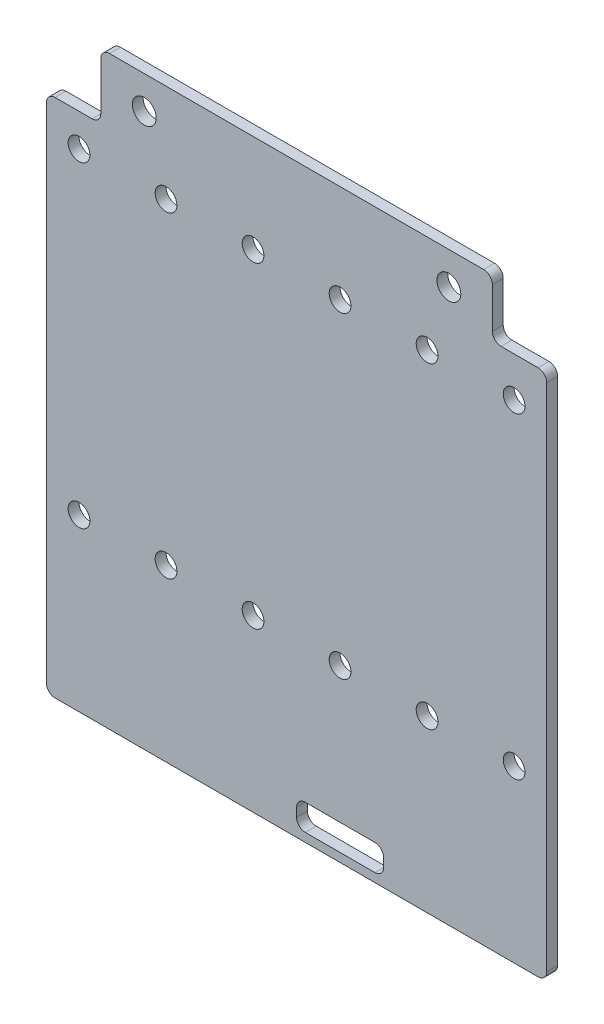
SolidWorks part; units mm, degrees
ref_plane "Front Plane" through (0, 0, 0) normal (0, 0, 1) x (1, 0, 0)
ref_plane "Top Plane" through (0, 0, 0) normal (0, 1, 0) x (1, 0, 0)
ref_plane "Right Plane" through (0, 0, 0) normal (1, 0, 0) x (0, 0, -1)
sketch "Sketch1" plane through (0, 0, 0) normal (0, 0, 1) x (1, 0, 0)
  line L0 (-63.5, -12.7) -> (63.5, -12.7) construction
  line L2 (-57.15, -3.175) -> (-57.15, 15.875)
  line L3 (-57.15, 15.875) -> (57.15, 15.875)
  line L4 (57.15, -1.0097) -> (57.15, 15.875)
  line L5 (-57.15, -3.175) -> (-73.025, -3.175)
  line L6 (-73.025, -3.175) -> (-73.025, -27.559)
  line L8 (73.025, -27.559) -> (73.025, -1.0097)
  line L9 (73.025, -1.0097) -> (57.15, -1.0097)
  line L10 (-44.45, 6.35) -> (44.45, 6.35) construction
  line L11 (-73.025, -27.559) -> (-73.025, -154.984)
  line L12 (-73.025, -154.984) -> (73.025, -154.984)
  line L13 (73.025, -154.984) -> (73.025, -27.559)
  line L17 (-63.5, -105.2) -> (63.5, -105.2) construction
  circle A0 centre (-44.45, 6.35) radius 3.4925
  circle A1 centre (44.45, 6.35) radius 3.4925
  circle A2 centre (-63.5, -12.7) radius 3.175
  circle A3 centre (-38.1, -12.7) radius 3.175
  circle A4 centre (-12.7, -12.7) radius 3.175
  circle A5 centre (12.7, -12.7) radius 3.175
  circle A6 centre (38.1, -12.7) radius 3.175
  circle A7 centre (63.5, -12.7) radius 3.175
  circle A8 centre (-63.5, -105.2) radius 3.175
  circle A9 centre (-38.1, -105.2) radius 3.175
  circle A10 centre (-12.7, -105.2) radius 3.175
  circle A11 centre (12.7, -105.2) radius 3.175
  circle A12 centre (38.1, -105.2) radius 3.175
  circle A13 centre (63.5, -105.2) radius 3.175
  point P0 (0, 0)
  point P12 (0, -12.7)
  point P27 (0, 15.875)
  dimension "D1" = 6.985
  dimension "D2" = 6.35
  dimension "0." = 6.985
  dimension "D7" = 6
  dimension "D15" = 6.35
  dimension "D3" = 88.9
  dimension "D4" = 114.3
  dimension "D5" = 0
  dimension "D6" = 146.05
  dimension "D8" = 0
  dimension "D9" = 9.525
  dimension "D10" = 28.575
  dimension "D11" = 9.525
  dimension "D14" = 92.5
  dimension "D18" = 49.784
  dimension "D16" = 6
extrude "Boss-Extrude1" add sketch "Sketch1" along normal blind 3.175
fillet "Fillet2" radius 2.54 6 edges at (57.15, 15.875, 1.5875) (73.025, -1.0097, 1.5875) (73.025, -154.984, 1.5875) (-73.025, -154.984, 1.5875) (-73.025, -3.175, 1.5875) (-57.15, 15.875, 1.5875)
sketch "Sketch3" plane through (0, 0, 3.175) normal (0, 0, 1) x (1, 0, 0)
  line L0 (-44.45, 6.35) -> (130.219, -168.319) construction
  line L1 (-44.45, 6.35) -> (44.45, 6.35) construction
  line L2 (44.45, 6.35) -> (86.36, -35.56) construction
  line L3 (73.025, -17.1806) -> (99.695, -17.1806)
  line L4 (73.025, -152.444) -> (73.025, -3.5497) construction
  line L5 (99.695, -17.1806) -> (99.695, -181.654)
  line L6 (99.695, -181.654) -> (60.042, -181.654)
  line L7 (60.042, -181.654) -> (60.042, -154.984)
  line L8 (-70.485, -154.984) -> (70.485, -154.984) construction
  line L9 (60.042, -154.984) -> (70.485, -154.984)
  line L10 (73.025, -152.444) -> (73.025, -17.1806)
  arc A0 (70.485, -154.984) -> (73.025, -152.444) centre (70.485, -152.444) ccw
  circle A1 centre (130.219, -168.319) radius 6.985
  circle A2 centre (86.36, -35.56) radius 6.985
  dimension "D3" = 13.335
  dimension "D4" = 13.335
  dimension "D1" = 45
  dimension "D2" = 135
  dimension "D5" = 13.335
  dimension "D6" = 13.335
fillet "Fillet3" radius 2.54 2 edges at (-57.15, -3.175, 1.5875) (57.15, -1.0097, 1.5875)
sketch "Sketch4" plane through (0, 0, 0) normal (0, 0, -1) x (-1, 0, 0)
  line L0 (-12.7, -105.2) -> (-12.7, -148.634) construction
  line L1 (70.485, -154.984) -> (-70.485, -154.984) construction
  line L3 (-25.4, -144.824) -> (0, -144.824)
  line L4 (-25.4, -144.824) -> (-25.4, -152.444)
  line L5 (-25.4, -152.444) -> (0, -152.444)
  line L6 (0, -144.824) -> (0, -152.444)
  line L7 (-25.4, -144.824) -> (0, -152.444) construction
  line L8 (-25.4, -152.444) -> (0, -144.824) construction
  dimension "D1" = 7.62
  dimension "0.2" = 6.35
  dimension "D2" = 25.4
extrude "Cut-Extrude1" cut sketch "Sketch4" against normal through all
fillet "Fillet4" radius 2.54 4 edges at (0, -152.444, 1.5875) (0, -144.824, 1.5875) (25.4, -152.444, 1.5875) (25.4, -144.824, 1.5875)
